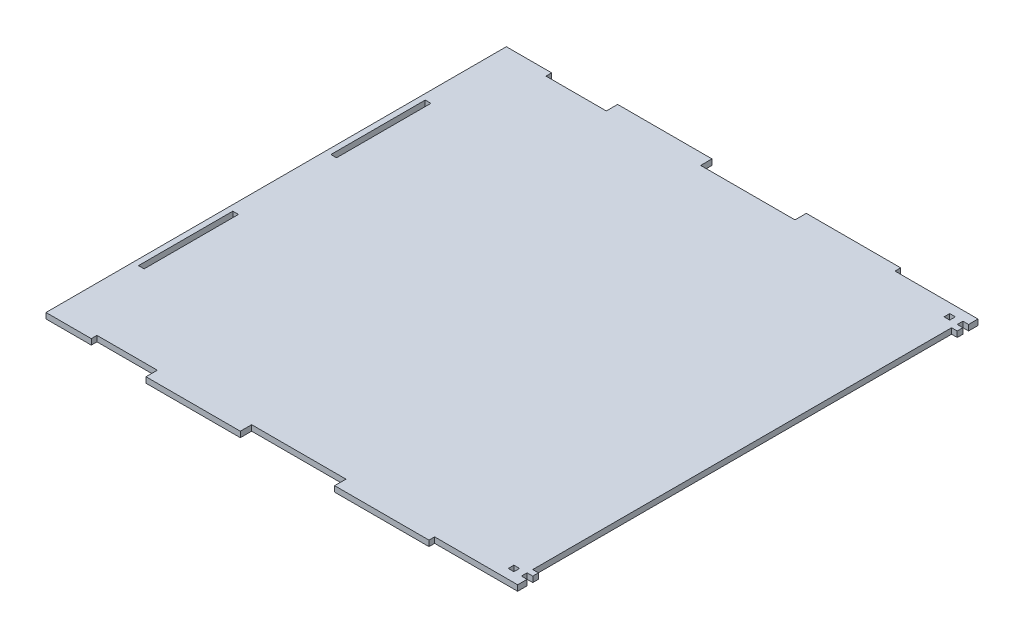
SolidWorks part; units mm, degrees
ref_plane "Front Plane" through (0, 0, 0) normal (0, 0, 1) x (1, 0, 0)
ref_plane "Top Plane" through (0, 0, 0) normal (0, 1, 0) x (1, 0, 0)
ref_plane "Right Plane" through (0, 0, 0) normal (1, 0, 0) x (0, 0, -1)
sketch "Sketch1" plane through (0, 0, 0) normal (0, 1, 0) x (1, 0, 0)
  line L0 (247, -244) -> (247, -239)
  line L1 (0, -244) -> (21, -244)
  line L2 (0, -148) -> (0, -198)
  line L3 (0, 0) -> (21, 0)
  line L4 (53, 3) -> (53, -3)
  line L5 (244, -233) -> (244, -11)
  line L6 (103, 3) -> (103, -3)
  line L7 (53, 3) -> (103, 3)
  line L8 (153, -3) -> (153, 3)
  line L9 (237, -5) -> (240, -5)
  line L10 (203, 0) -> (247, 0)
  line L11 (237, -5) -> (237, -8)
  line L12 (237, -8) -> (240, -8)
  line L13 (203, -244) -> (247, -244)
  line L14 (203, -244) -> (203, -247)
  line L15 (153, -247) -> (203, -247)
  line L16 (247, -11) -> (247, -8)
  line L17 (0, -46) -> (3, -46)
  line L18 (3, -198) -> (0, -198)
  line L19 (0, -96) -> (3, -96)
  line L20 (3, -46) -> (3, -96)
  line L21 (240, -5) -> (240, -8)
  line L22 (53, -241) -> (53, -247)
  line L23 (103, -247) -> (53, -247)
  line L25 (103, -247) -> (103, -241)
  line L26 (203, 3) -> (203, 0)
  line L27 (153, 3) -> (203, 3)
  line L28 (103, -241) -> (153, -241)
  line L29 (244, -236) -> (247, -236)
  line L30 (244, -236) -> (244, -239)
  line L31 (244, -5) -> (247, -5)
  line L32 (244, -5) -> (244, -8)
  line L33 (0, -148) -> (3, -148)
  line L34 (153, -247) -> (153, -241)
  line L36 (3, -148) -> (3, -198)
  line L37 (247, -5) -> (247, 0)
  line L38 (247, -236) -> (247, -233)
  line L40 (0, 0) -> (-3, 0)
  line L41 (0, -46) -> (0, -96)
  line L42 (0, -244) -> (-3, -244)
  line L43 (-3, 0) -> (-3, -244)
  line L55 (244, -233) -> (247, -233)
  line L57 (244, -11) -> (247, -11)
  line L62 (53, -3) -> (21, -3)
  line L63 (21, 0) -> (21, -3)
  line L67 (103, -3) -> (153, -3)
  line L69 (244, -239) -> (247, -239)
  line L70 (237, -236) -> (240, -236)
  line L71 (237, -236) -> (237, -239)
  line L72 (237, -239) -> (240, -239)
  line L73 (240, -236) -> (240, -239)
  line L75 (21, -244) -> (21, -241)
  line L76 (244, -8) -> (247, -8)
  line L78 (21, -241) -> (53, -241)
  dimension "D1" = 247
  dimension "D3" = 50
  dimension "D5" = 52
  dimension "D6" = 50
  dimension "D7" = 3
  dimension "D8" = 6
  dimension "D9" = 44
  dimension "D10" = 4
  dimension "D11" = 32
  dimension "D12" = 6
  dimension "D13" = 50
  dimension "D14" = 222
  dimension "D15" = 3
  dimension "D16" = 50
  dimension "D17" = 3
  dimension "D18" = 6
  dimension "D19" = 3
  dimension "D20" = 3
  dimension "D21" = 3
  dimension "D22" = 5
  dimension "D23" = 4
  dimension "D24" = 3
  dimension "D25" = 244
  dimension "D26" = 3
  dimension "D27" = 46
  dimension "D28" = 3
  dimension "D29" = 44
  dimension "D30" = 3
  dimension "D31" = 3
  dimension "D32" = 21
  dimension "D33" = 5
  dimension "D35" = 3
  dimension "D36" = 50
  dimension "D37" = 3
  dimension "D38" = 5
  dimension "D40" = 32
  dimension "D41" = 21
  dimension "D44" = 50
  dimension "D45" = 50
extrude "Boss-Extrude1" add sketch "Sketch1" along normal blind 3
equation "\"w\"=3"
equation "\"L\"=50"
